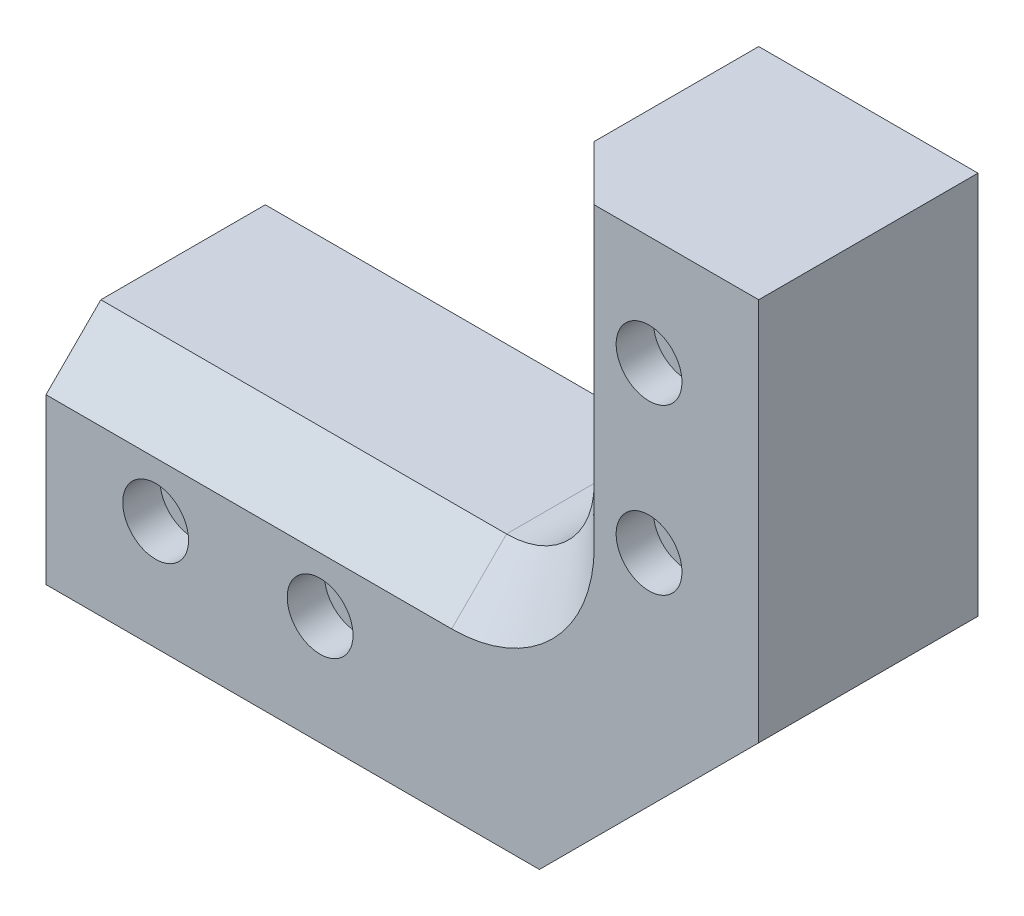
SolidWorks part; units mm, degrees
material "AISI Type 316L stainless steel"
ref_plane "Front Plane" through (0, 0, 0) normal (0, 0, 1) x (1, 0, 0)
ref_plane "Top Plane" through (0, 0, 0) normal (0, 1, 0) x (1, 0, 0)
ref_plane "Right Plane" through (0, 0, 0) normal (1, 0, 0) x (0, 0, -1)
sketch "Sketch1" plane through (0, 0, 0) normal (0, 0, 1) x (1, 0, 0)
  line L0 (0, 0) -> (-45, 0)
  line L1 (-45, 0) -> (-45, -20)
  line L2 (-45, -20) -> (20, -20)
  line L3 (20, -20) -> (20, 35)
  line L4 (20, 35) -> (0, 35)
  line L5 (0, 35) -> (0, 0)
  line L6 (0, 0) -> (20, -20) construction
  point P6 (-20, -10)
  point P7 (11.7127, 0)
  point P8 (-20, -10)
  point P9 (-35, -10)
  point P12 (10, -10)
  point P15 (10, 25)
  point P17 (10, 10)
  dimension "D1" = 15
  dimension "D2" = 20
  dimension "D3" = 20
  dimension "D4" = 20
  dimension "D5" = 35
  dimension "D6" = 45
  dimension "D7" = 10
  dimension "D8" = 30
  dimension "D9" = 15
extrude "Boss-Extrude1" add sketch "Sketch1" along normal blind 20
sketch "Sketch2" plane through (0, 0, 20) normal (0, 0, 1) x (1, 0, 0)
  point P0 (-35, -10)
  point P1 (-20, -10)
  point P2 (10, 25)
  point P13 (10, 10)
hole_wizard "CBORE for M3 Hexagon socket head cap screws1" positions "Sketch3" profile "Sketch5" counterbore size "M3" standard "GB" end condition through all
sketch "Sketch3" plane through (0, 0, 20) normal (0, 0, 1) x (1, 0, 0)
  point P0 (-35, -10)
  point P3 (-20, -10)
  point P6 (10, 25)
  point P10 (10, 10)
  point P17 (0, 0)
sketch "Sketch5" plane through (-35, -10, 20) normal (1, 0, 0) x (0, -1, 0)
  line L0 (0, 0) -> (0, 20)
  line L1 (0, 20) -> (1.6, 20)
  line L3 (1.6, 20) -> (1.6, 3.4)
  line L4 (1.6, 3.4) -> (3, 3.4)
  line L5 (3, 3.4) -> (3, 0)
  line L7 (3, 0) -> (0, 0)
  line L11 (0, -6.35) -> (0, 107.95) construction
  dimension "Thru Hole Dia." = 3.2
  dimension "Thru Hole Depth" = 20
  dimension "C'Bore Dia." = 6
  dimension "C'Bore Depth" = 3.4
fillet "Fillet1" radius 8 1 edges at (0, 0, 10)
chamfer "Chamfer1" distance 20 angle 45 1 edges at (20, -20, 10)
hole_wizard "M6 Tapped Hole1" positions "Sketch6" profile "Sketch7" tap size "M6" standard "GB" end condition through all
sketch "Sketch6" plane through (10, -10, 0) normal (0.7071, -0.7071, 0) x (-0.7071, -0.7071, 0)
  line L1 (0, 0) -> (0, -20) construction
  line L2 (-14.1421, 0) -> (14.1421, 0) construction
  line L3 (14.1421, -20) -> (-14.1421, -20) construction
  line L4 (-14.1421, 0) -> (-38.8909, 0) construction
  point P0 (0, -10)
  point P13 (0, 0)
  dimension "D1" = 10
sketch "Sketch7" plane through (10, -10, 10) normal (0, 0, 1) x (0.7071, 0.7071, 0)
  line L0 (0, 0) -> (0, 70.7107)
  line L1 (0, 70.7107) -> (2.5, 70.7107)
  line L2 (2.5, 70.7107) -> (2.5, 0.525)
  line L3 (2.5, 0.525) -> (3.025, 0)
  line L5 (3.025, 0) -> (0, 0)
  line L6 (-2.5, 0.525) -> (-3.025, 0) construction
  line L11 (0, -6.35) -> (0, 107.95) construction
  dimension "Thru Tap Drill Dia." = 5
  dimension "Thru Tap Drill Depth" = 70.7107
  dimension "Near C'Sink Dia." = 6.05
  dimension "Near C'Sink Angle" = 90
chamfer "Chamfer2" distance 5 angle 45 3 edges at (0, 21.5, 20) (-26.5, 0, 20) (-2.3431, 2.3431, 20)
